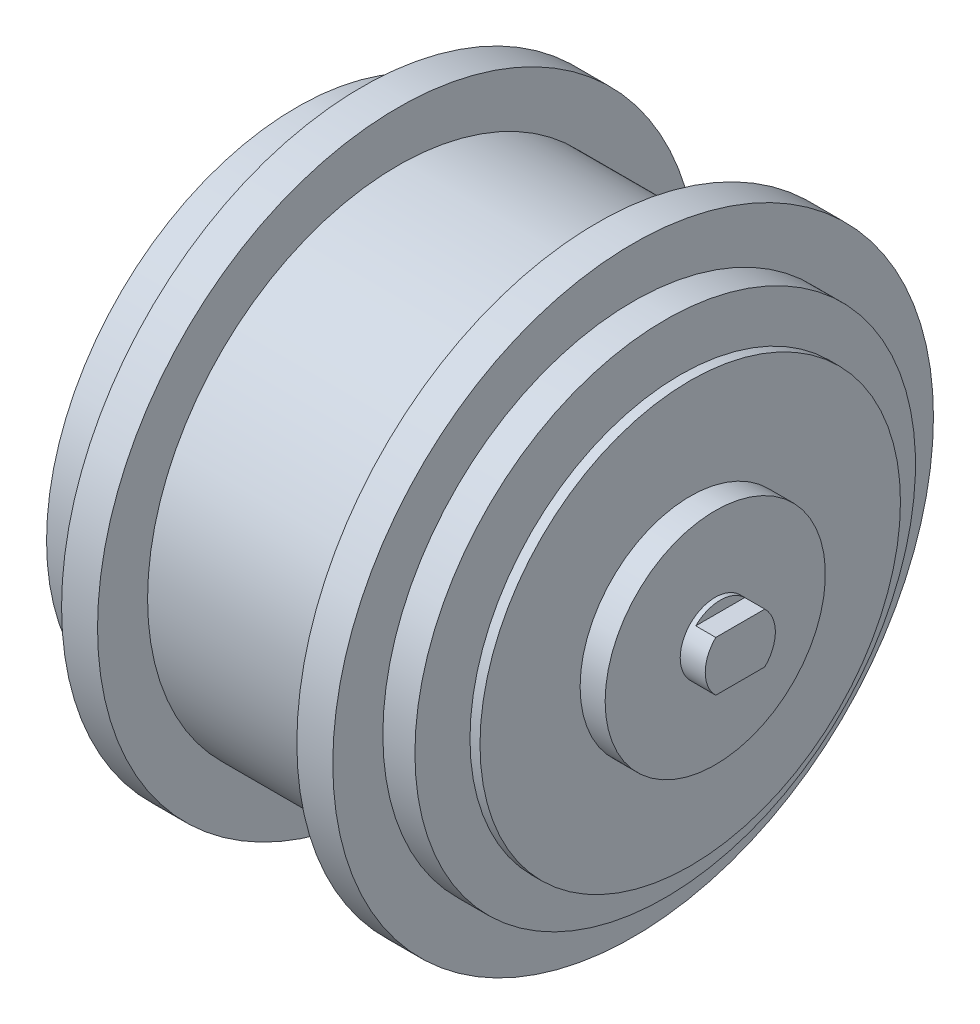
SolidWorks part; units mm, degrees
ref_plane "Front Plane" through (0, 0, 0) normal (0, 0, 1) x (1, 0, 0)
ref_plane "Top Plane" through (0, 0, 0) normal (0, 1, 0) x (1, 0, 0)
ref_plane "Right Plane" through (0, 0, 0) normal (1, 0, 0) x (0, 0, -1)
sketch "Sketch1" plane through (0, 0, 0) normal (0, 0, 1) x (1, 0, 0)
  line L0 (0, 0) -> (219.0485, 0) construction
  line L1 (0, 0) -> (0, 6)
  line L2 (0, 6) -> (33, 6)
  line L3 (33, 6) -> (33, 8.5)
  line L4 (33, 8.5) -> (43.5, 8.5)
  line L5 (66.569, 50) -> (66.569, 60)
  line L6 (73.751, 60) -> (66.569, 60)
  line L7 (73.751, 60) -> (73.751, 50)
  line L8 (66.569, 50) -> (53.569, 50)
  line L9 (53.569, 50) -> (46.5, 36.3186)
  line L10 (43.5, 8.5) -> (43.5, 17)
  line L11 (43.5, 17) -> (46.5, 17)
  line L12 (46.5, 17) -> (46.5, 36.3186)
  line L13 (73.751, 50) -> (113.569, 50)
  line L14 (113.569, 50) -> (113.569, 60)
  line L15 (113.569, 60) -> (120.751, 60)
  line L16 (120.751, 60) -> (120.751, 50)
  line L17 (120.751, 50) -> (127.16, 50)
  line L18 (127.16, 50) -> (127.16, 22)
  line L19 (127.16, 22) -> (130.16, 22)
  line L20 (137.16, 22) -> (137.16, 7)
  line L21 (137.16, 7) -> (142.16, 7)
  line L22 (142.16, 7) -> (142.16, 0)
  line L23 (130.16, 22) -> (130.16, 42)
  line L24 (130.16, 42) -> (132.16, 42)
  line L25 (142.16, 0) -> (0, 0)
  line L26 (132.16, 42) -> (132.16, 22)
  line L27 (132.16, 22) -> (137.16, 22)
  point P13 (70.16, 60)
  point P23 (117.16, 60)
  dimension "D1" = 33
  dimension "D2" = 8.5
  dimension "D3" = 10.5
  dimension "D4" = 26.66
  dimension "D5" = 60
  dimension "D6" = 10
  dimension "D7" = 13
  dimension "D9" = 47
  dimension "D10" = 10
  dimension "D11" = 22
  dimension "D12" = 10
  dimension "D13" = 6
  dimension "D14" = 5
  dimension "D15" = 2
  dimension "D16" = 7
  dimension "D17" = 5
  dimension "D18" = 20
revolve "Revolve1" add sketch "Sketch1" angle 360 about L0
sketch "Sketch2" plane through (142.16, 0, 0) normal (1, 0, 0) x (0, 0, -1)
  line L0 (-4.899, 5) -> (4.899, 5)
  line L1 (-4.899, -5) -> (4.899, -5)
  circle A0 centre (0, 0) radius 7 construction
  circle A1 centre (0, 0) radius 7 construction
  arc A2 (-4.899, -5) -> (4.899, -5) centre (0, 0) ccw
  arc A3 (4.899, 5) -> (-4.899, 5) centre (0, 0) ccw
  dimension "D1" = 10
extrude "Cut-Extrude1" cut sketch "Sketch2" against normal blind 4
sketch "Sketch3" plane through (33, 0, 0) normal (-1, 0, 0) x (0, 0, 1)
  circle A0 centre (0, 0) radius 8.5 construction
  circle A1 centre (0, 0) radius 8.5
extrude "Cut-Extrude2" cut sketch "Sketch3" against normal blind 3 and the other way through all
